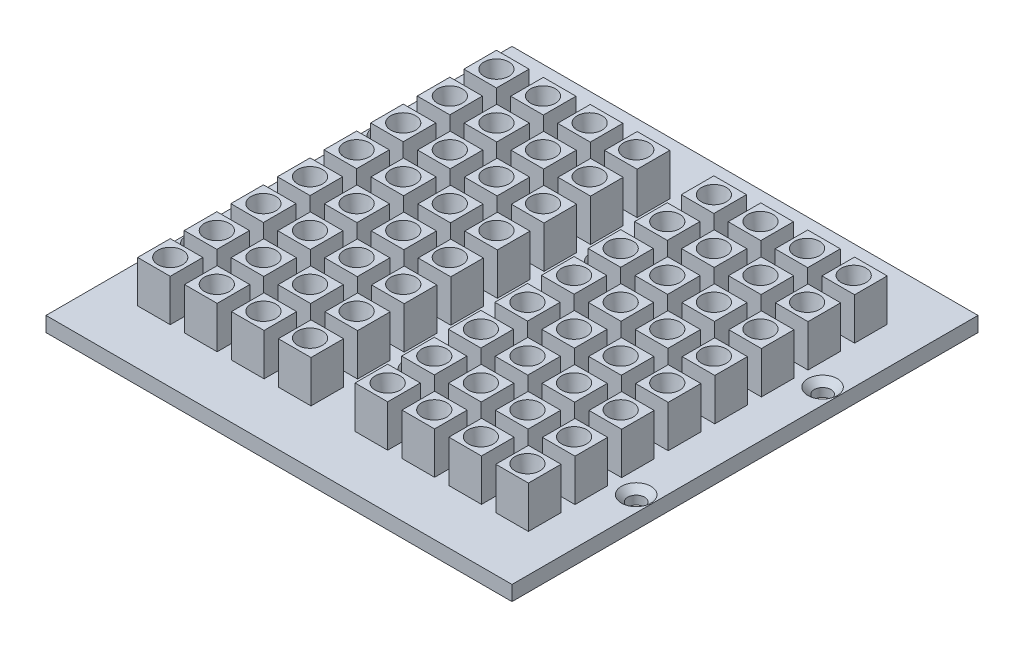
SolidWorks part; units mm, degrees
ref_plane "Front Plane" through (0, 0, 0) normal (0, 0, 1) x (1, 0, 0)
ref_plane "Top Plane" through (0, 0, 0) normal (0, 1, 0) x (1, 0, 0)
ref_plane "Right Plane" through (0, 0, 0) normal (1, 0, 0) x (0, 0, -1)
sketch "Sketch1" plane through (0, 0, 0) normal (0, 1, 0) x (1, 0, 0)
  line L1 (0, 0) -> (122, 0)
  line L2 (0, 0) -> (0, 100)
  line L3 (0, 100) -> (122, 100)
  line L4 (122, 0) -> (122, 100)
  dimension "D1" = 122
  dimension "D2" = 100
extrude "Boss-Extrude1" add sketch "Sketch1" along normal blind 3.2
sketch "Heatsink size" plane through (0, 3.2, 0) normal (0, 1, 0) x (1, 0, 0)
  line L0 (0, 100) -> (0, 0) construction
  line L1 (11, 100) -> (111, 100)
  line L2 (11, 100) -> (11, 0)
  line L3 (11, 0) -> (111, 0)
  line L4 (111, 100) -> (111, 0)
  line L5 (122, 100) -> (0, 100) construction
  dimension "D1" = 100
  dimension "D2" = 100
  dimension "D3" = 11
  dimension "D4" = 0
sketch "Peltiers" plane through (0, 3.2, 0) normal (0, 1, 0) x (1, 0, 0)
  line L0 (11, 100) -> (111, 100) construction
  line L1 (17.66, 90) -> (57.66, 90)
  line L2 (17.66, 90) -> (17.66, 50)
  line L3 (17.66, 50) -> (57.66, 50)
  line L4 (57.66, 90) -> (57.66, 50)
  line L5 (11, 100) -> (11, 0) construction
  line L6 (64.32, 90) -> (64.32, 50)
  line L7 (64.32, 90) -> (104.32, 90)
  line L8 (104.32, 90) -> (104.32, 50)
  line L9 (64.32, 50) -> (104.32, 50)
  line L10 (64.32, 50) -> (64.32, 10)
  line L11 (64.32, 50) -> (104.32, 50)
  line L12 (104.32, 50) -> (104.32, 10)
  line L13 (64.32, 10) -> (104.32, 10)
  line L14 (17.66, 50) -> (17.66, 10)
  line L15 (17.66, 50) -> (57.66, 50)
  line L16 (57.66, 50) -> (57.66, 10)
  line L17 (17.66, 10) -> (57.66, 10)
  line L18 (17.66, 90) -> (64.32, 90) construction
  dimension "D1" = 40
  dimension "D2" = 40
  dimension "D3" = 10
  dimension "D4" = 6.66
  dimension "D6" = 46.66
  dimension "D5" = 2
  dimension "D7" = 2
sketch "Sketch4" plane through (0, 3.2, 0) normal (0, 1, 0) x (1, 0, 0)
  line L0 (11, 100) -> (111, 100) construction
  line L1 (11, 100) -> (11, 0) construction
  line L2 (14.33, 70) -> (60.99, 70) construction
  circle A0 centre (14.33, 70) radius 2
  circle A1 centre (60.99, 70) radius 2
  circle A2 centre (107.65, 70) radius 2
  circle A3 centre (60.99, 30) radius 2
  circle A4 centre (107.65, 30) radius 2
  circle A5 centre (14.33, 30) radius 2
  dimension "D1" = 30
  dimension "D2" = 3.33
  dimension "D4" = 46.66
  dimension "D3" = 3
hole_wizard "M3 Block Mounting holes" positions "3DSketch1" profile "Sketch5" countersink size "M3" standard "ANSI Metric" end condition through all
sketch3d "3DSketch1"
  point P0 (14.33, 3.2, -70)
  point P3 (60.99, 3.2, -70)
  point P6 (107.65, 3.2, -70)
  point P9 (107.65, 3.2, -30)
  point P12 (60.99, 3.2, -30)
  point P15 (14.33, 3.2, -30)
sketch "Sketch5" plane through (14.33, 3.2, -70) normal (1, 0, 0) x (0, 0, 1)
  line L0 (0, 0) -> (0, 3.2)
  line L1 (0, 3.2) -> (1.8, 3.2)
  line L2 (1.8, 3.2) -> (1.8, 1.35)
  line L3 (1.8, 1.35) -> (3.15, 0)
  line L5 (3.15, 0) -> (0, 0)
  line L6 (-1.8, 1.35) -> (-3.15, 0) construction
  line L11 (0, -6.35) -> (0, 107.95) construction
  dimension "Thru Hole Dia." = 3.6
  dimension "Thru Hole Depth" = 3.2
  dimension "Near C'Sink Dia." = 6.3
  dimension "Near C'Sink Angle" = 90
sketch "Sketch6" plane through (0, 3.2, 0) normal (0, 1, 0) x (1, 0, 0)
  line L0 (0, 100) -> (0, 0) construction
  line L1 (122, 100) -> (0, 100) construction
  circle A0 centre (5, 94) radius 2.4675
  circle A1 centre (117, 94) radius 2.4675
  circle A2 centre (117, 7) radius 2.4675
  circle A3 centre (5, 7) radius 2.4675
  dimension "D1" = 5
  dimension "D2" = 6
  dimension "D3" = 2
hole_wizard "M3 Hsink Mounting holes" [suppressed] positions "3DSketch2" profile "Sketch7" countersink size "M3" standard "ANSI Metric"
sketch3d "3DSketch2" [suppressed]
  point P0 (5, 3.2, -94)
  point P3 (117, 3.2, -94)
  point P6 (117, 3.2, -7)
  point P9 (5, 3.2, -7)
sketch "Sketch7" [suppressed] plane through (5, 3.2, -94) normal (1, 0, 0) x (0, 0, 1)
  line L0 (0, 0) -> (0, 3.2)
  line L1 (0, 3.2) -> (1.8, 3.2)
  line L2 (1.8, 3.2) -> (1.8, 1.35)
  line L3 (1.8, 1.35) -> (3.15, 0)
  line L5 (3.15, 0) -> (0, 0)
  line L6 (-1.8, 1.35) -> (-3.15, 0) construction
  line L11 (0, -6.35) -> (0, 107.95) construction
  dimension "Thru Hole Dia." = 3.6
  dimension "Thru Hole Depth" = 3.2
  dimension "Near C'Sink Dia." = 6.3
  dimension "Near C'Sink Angle" = 90
sketch "WellsSquare" plane through (0, 3.2, 0) normal (0, 1, 0) x (1, 0, 0)
  line L0 (17.66, 90) -> (57.66, 90) construction
  line L1 (19.06, 88.6) -> (26.06, 88.6)
  line L2 (19.06, 88.6) -> (19.06, 81.6)
  line L3 (19.06, 81.6) -> (26.06, 81.6)
  line L4 (26.06, 88.6) -> (26.06, 81.6)
  line L5 (17.66, 90) -> (17.66, 50) construction
  line L6 (29.1267, 88.6) -> (29.1267, 81.6)
  line L7 (29.1267, 88.6) -> (36.1267, 88.6)
  line L8 (36.1267, 88.6) -> (36.1267, 81.6)
  line L9 (29.1267, 81.6) -> (36.1267, 81.6)
  line L10 (39.1933, 88.6) -> (39.1933, 81.6)
  line L11 (39.1933, 88.6) -> (46.1933, 88.6)
  line L12 (46.1933, 88.6) -> (46.1933, 81.6)
  line L13 (39.1933, 81.6) -> (46.1933, 81.6)
  line L14 (49.26, 88.6) -> (49.26, 81.6)
  line L15 (49.26, 88.6) -> (56.26, 88.6)
  line L16 (56.26, 88.6) -> (56.26, 81.6)
  line L17 (49.26, 81.6) -> (56.26, 81.6)
  line L18 (29.1267, 78.6) -> (29.1267, 71.6)
  line L19 (29.1267, 78.6) -> (36.1267, 78.6)
  line L20 (36.1267, 78.6) -> (36.1267, 71.6)
  line L21 (29.1267, 71.6) -> (36.1267, 71.6)
  line L22 (39.1933, 78.6) -> (39.1933, 71.6)
  line L23 (39.1933, 78.6) -> (46.1933, 78.6)
  line L24 (46.1933, 78.6) -> (46.1933, 71.6)
  line L25 (39.1933, 71.6) -> (46.1933, 71.6)
  line L26 (49.26, 78.6) -> (49.26, 71.6)
  line L27 (49.26, 78.6) -> (56.26, 78.6)
  line L28 (56.26, 78.6) -> (56.26, 71.6)
  line L29 (49.26, 71.6) -> (56.26, 71.6)
  line L30 (29.1267, 68.6) -> (29.1267, 61.6)
  line L31 (29.1267, 68.6) -> (36.1267, 68.6)
  line L32 (36.1267, 68.6) -> (36.1267, 61.6)
  line L33 (29.1267, 61.6) -> (36.1267, 61.6)
  line L34 (39.1933, 68.6) -> (39.1933, 61.6)
  line L35 (39.1933, 68.6) -> (46.1933, 68.6)
  line L36 (46.1933, 68.6) -> (46.1933, 61.6)
  line L37 (39.1933, 61.6) -> (46.1933, 61.6)
  line L38 (49.26, 68.6) -> (49.26, 61.6)
  line L39 (49.26, 68.6) -> (56.26, 68.6)
  line L40 (56.26, 68.6) -> (56.26, 61.6)
  line L41 (49.26, 61.6) -> (56.26, 61.6)
  line L42 (29.1267, 58.6) -> (29.1267, 51.6)
  line L43 (29.1267, 58.6) -> (36.1267, 58.6)
  line L44 (36.1267, 58.6) -> (36.1267, 51.6)
  line L45 (29.1267, 51.6) -> (36.1267, 51.6)
  line L46 (39.1933, 58.6) -> (39.1933, 51.6)
  line L47 (39.1933, 58.6) -> (46.1933, 58.6)
  line L48 (46.1933, 58.6) -> (46.1933, 51.6)
  line L49 (39.1933, 51.6) -> (46.1933, 51.6)
  line L50 (49.26, 58.6) -> (49.26, 51.6)
  line L51 (49.26, 58.6) -> (56.26, 58.6)
  line L52 (56.26, 58.6) -> (56.26, 51.6)
  line L53 (49.26, 51.6) -> (56.26, 51.6)
  line L54 (29.1267, 48.6) -> (29.1267, 41.6)
  line L55 (29.1267, 48.6) -> (36.1267, 48.6)
  line L56 (36.1267, 48.6) -> (36.1267, 41.6)
  line L57 (29.1267, 41.6) -> (36.1267, 41.6)
  line L58 (39.1933, 48.6) -> (39.1933, 41.6)
  line L59 (39.1933, 48.6) -> (46.1933, 48.6)
  line L60 (46.1933, 48.6) -> (46.1933, 41.6)
  line L61 (39.1933, 41.6) -> (46.1933, 41.6)
  line L62 (49.26, 48.6) -> (49.26, 41.6)
  line L63 (49.26, 48.6) -> (56.26, 48.6)
  line L64 (56.26, 48.6) -> (56.26, 41.6)
  line L65 (49.26, 41.6) -> (56.26, 41.6)
  line L66 (29.1267, 38.6) -> (29.1267, 31.6)
  line L67 (29.1267, 38.6) -> (36.1267, 38.6)
  line L68 (36.1267, 38.6) -> (36.1267, 31.6)
  line L69 (29.1267, 31.6) -> (36.1267, 31.6)
  line L70 (39.1933, 38.6) -> (39.1933, 31.6)
  line L71 (39.1933, 38.6) -> (46.1933, 38.6)
  line L72 (46.1933, 38.6) -> (46.1933, 31.6)
  line L73 (39.1933, 31.6) -> (46.1933, 31.6)
  line L74 (49.26, 38.6) -> (49.26, 31.6)
  line L75 (49.26, 38.6) -> (56.26, 38.6)
  line L76 (56.26, 38.6) -> (56.26, 31.6)
  line L77 (49.26, 31.6) -> (56.26, 31.6)
  line L78 (29.1267, 28.6) -> (29.1267, 21.6)
  line L79 (29.1267, 28.6) -> (36.1267, 28.6)
  line L80 (36.1267, 28.6) -> (36.1267, 21.6)
  line L81 (29.1267, 21.6) -> (36.1267, 21.6)
  line L82 (39.1933, 28.6) -> (39.1933, 21.6)
  line L83 (39.1933, 28.6) -> (46.1933, 28.6)
  line L84 (46.1933, 28.6) -> (46.1933, 21.6)
  line L85 (39.1933, 21.6) -> (46.1933, 21.6)
  line L86 (49.26, 28.6) -> (49.26, 21.6)
  line L87 (49.26, 28.6) -> (56.26, 28.6)
  line L88 (56.26, 28.6) -> (56.26, 21.6)
  line L89 (49.26, 21.6) -> (56.26, 21.6)
  line L90 (29.1267, 18.6) -> (29.1267, 11.6)
  line L91 (29.1267, 18.6) -> (36.1267, 18.6)
  line L92 (36.1267, 18.6) -> (36.1267, 11.6)
  line L93 (29.1267, 11.6) -> (36.1267, 11.6)
  line L94 (39.1933, 18.6) -> (39.1933, 11.6)
  line L95 (39.1933, 18.6) -> (46.1933, 18.6)
  line L96 (46.1933, 18.6) -> (46.1933, 11.6)
  line L97 (39.1933, 11.6) -> (46.1933, 11.6)
  line L98 (49.26, 18.6) -> (49.26, 11.6)
  line L99 (49.26, 18.6) -> (56.26, 18.6)
  line L100 (56.26, 18.6) -> (56.26, 11.6)
  line L101 (49.26, 11.6) -> (56.26, 11.6)
  line L102 (19.06, 78.6) -> (19.06, 71.6)
  line L103 (19.06, 78.6) -> (26.06, 78.6)
  line L104 (26.06, 78.6) -> (26.06, 71.6)
  line L105 (19.06, 71.6) -> (26.06, 71.6)
  line L106 (19.06, 68.6) -> (19.06, 61.6)
  line L107 (19.06, 68.6) -> (26.06, 68.6)
  line L108 (26.06, 68.6) -> (26.06, 61.6)
  line L109 (19.06, 61.6) -> (26.06, 61.6)
  line L110 (19.06, 58.6) -> (19.06, 51.6)
  line L111 (19.06, 58.6) -> (26.06, 58.6)
  line L112 (26.06, 58.6) -> (26.06, 51.6)
  line L113 (19.06, 51.6) -> (26.06, 51.6)
  line L114 (19.06, 48.6) -> (19.06, 41.6)
  line L115 (19.06, 48.6) -> (26.06, 48.6)
  line L116 (26.06, 48.6) -> (26.06, 41.6)
  line L117 (19.06, 41.6) -> (26.06, 41.6)
  line L118 (19.06, 38.6) -> (19.06, 31.6)
  line L119 (19.06, 38.6) -> (26.06, 38.6)
  line L120 (26.06, 38.6) -> (26.06, 31.6)
  line L121 (19.06, 31.6) -> (26.06, 31.6)
  line L122 (19.06, 28.6) -> (19.06, 21.6)
  line L123 (19.06, 28.6) -> (26.06, 28.6)
  line L124 (26.06, 28.6) -> (26.06, 21.6)
  line L125 (19.06, 21.6) -> (26.06, 21.6)
  line L126 (19.06, 18.6) -> (19.06, 11.6)
  line L127 (19.06, 18.6) -> (26.06, 18.6)
  line L128 (26.06, 18.6) -> (26.06, 11.6)
  line L129 (19.06, 11.6) -> (26.06, 11.6)
  dimension "D1" = 7
  dimension "D2" = 7
  dimension "D3" = 1.4
  dimension "D4" = 1.4
  dimension "D5" = 4
  dimension "D6" = 8
extrude "Boss-Extrude4" add sketch "WellsSquare" along normal blind 9
sketch "WellHoles" plane through (0, 12.2, 0) normal (0, 1, 0) x (1, 0, 0)
  line L0 (19.06, 81.6) -> (26.06, 81.6) construction
  line L1 (26.06, 81.6) -> (26.06, 88.6) construction
  circle A0 centre (22.56, 85.1) radius 2.676
  circle A1 centre (32.56, 85.1) radius 2.676
  circle A2 centre (42.56, 85.1) radius 2.676
  circle A3 centre (52.56, 85.1) radius 2.676
  circle A4 centre (32.56, 75.1) radius 2.676
  circle A5 centre (42.56, 75.1) radius 2.676
  circle A6 centre (52.56, 75.1) radius 2.676
  circle A7 centre (32.56, 65.1) radius 2.676
  circle A8 centre (42.56, 65.1) radius 2.676
  circle A9 centre (52.56, 65.1) radius 2.676
  circle A10 centre (32.56, 55.1) radius 2.676
  circle A11 centre (42.56, 55.1) radius 2.676
  circle A12 centre (52.56, 55.1) radius 2.676
  circle A13 centre (32.56, 45.1) radius 2.676
  circle A14 centre (42.56, 45.1) radius 2.676
  circle A15 centre (52.56, 45.1) radius 2.676
  circle A16 centre (32.56, 35.1) radius 2.676
  circle A17 centre (42.56, 35.1) radius 2.676
  circle A18 centre (52.56, 35.1) radius 2.676
  circle A19 centre (32.56, 25.1) radius 2.676
  circle A20 centre (42.56, 25.1) radius 2.676
  circle A21 centre (52.56, 25.1) radius 2.676
  circle A22 centre (32.56, 15.1) radius 2.676
  circle A23 centre (42.56, 15.1) radius 2.676
  circle A24 centre (52.56, 15.1) radius 2.676
  circle A25 centre (22.56, 75.1) radius 2.676
  circle A26 centre (22.56, 65.1) radius 2.676
  circle A27 centre (22.56, 55.1) radius 2.676
  circle A28 centre (22.56, 45.1) radius 2.676
  circle A29 centre (22.56, 35.1) radius 2.676
  circle A30 centre (22.56, 25.1) radius 2.676
  circle A31 centre (22.56, 15.1) radius 2.676
  point P4 (22.56, 81.6)
  dimension "D1" = 3.5
  dimension "D2" = 3.5
  dimension "D3" = 4
extrude "Cut-Extrude1" cut sketch "WellHoles" against normal blind 11.176 draft 8.75
sketch "Sketch16" plane through (0, 3.2, 0) normal (0, 1, 0) x (1, 0, 0)
  line L1 (65.72, 88.6) -> (72.72, 88.6)
  line L2 (65.72, 88.6) -> (65.72, 81.6)
  line L3 (65.72, 81.6) -> (72.72, 81.6)
  line L4 (72.72, 88.6) -> (72.72, 81.6)
  line L6 (75.7867, 88.6) -> (75.7867, 81.6)
  line L7 (75.7867, 88.6) -> (82.7867, 88.6)
  line L8 (82.7867, 88.6) -> (82.7867, 81.6)
  line L9 (75.7867, 81.6) -> (82.7867, 81.6)
  line L10 (85.8533, 88.6) -> (85.8533, 81.6)
  line L11 (85.8533, 88.6) -> (92.8533, 88.6)
  line L12 (92.8533, 88.6) -> (92.8533, 81.6)
  line L13 (85.8533, 81.6) -> (92.8533, 81.6)
  line L14 (95.92, 88.6) -> (95.92, 81.6)
  line L15 (95.92, 88.6) -> (102.92, 88.6)
  line L16 (102.92, 88.6) -> (102.92, 81.6)
  line L17 (95.92, 81.6) -> (102.92, 81.6)
  line L18 (75.7867, 78.6) -> (75.7867, 71.6)
  line L19 (75.7867, 78.6) -> (82.7867, 78.6)
  line L20 (82.7867, 78.6) -> (82.7867, 71.6)
  line L21 (75.7867, 71.6) -> (82.7867, 71.6)
  line L22 (85.8533, 78.6) -> (85.8533, 71.6)
  line L23 (85.8533, 78.6) -> (92.8533, 78.6)
  line L24 (92.8533, 78.6) -> (92.8533, 71.6)
  line L25 (85.8533, 71.6) -> (92.8533, 71.6)
  line L26 (95.92, 78.6) -> (95.92, 71.6)
  line L27 (95.92, 78.6) -> (102.92, 78.6)
  line L28 (102.92, 78.6) -> (102.92, 71.6)
  line L29 (95.92, 71.6) -> (102.92, 71.6)
  line L30 (75.7867, 68.6) -> (75.7867, 61.6)
  line L31 (75.7867, 68.6) -> (82.7867, 68.6)
  line L32 (82.7867, 68.6) -> (82.7867, 61.6)
  line L33 (75.7867, 61.6) -> (82.7867, 61.6)
  line L34 (85.8533, 68.6) -> (85.8533, 61.6)
  line L35 (85.8533, 68.6) -> (92.8533, 68.6)
  line L36 (92.8533, 68.6) -> (92.8533, 61.6)
  line L37 (85.8533, 61.6) -> (92.8533, 61.6)
  line L38 (95.92, 68.6) -> (95.92, 61.6)
  line L39 (95.92, 68.6) -> (102.92, 68.6)
  line L40 (102.92, 68.6) -> (102.92, 61.6)
  line L41 (95.92, 61.6) -> (102.92, 61.6)
  line L42 (75.7867, 58.6) -> (75.7867, 51.6)
  line L43 (75.7867, 58.6) -> (82.7867, 58.6)
  line L44 (82.7867, 58.6) -> (82.7867, 51.6)
  line L45 (75.7867, 51.6) -> (82.7867, 51.6)
  line L46 (85.8533, 58.6) -> (85.8533, 51.6)
  line L47 (85.8533, 58.6) -> (92.8533, 58.6)
  line L48 (92.8533, 58.6) -> (92.8533, 51.6)
  line L49 (85.8533, 51.6) -> (92.8533, 51.6)
  line L50 (95.92, 58.6) -> (95.92, 51.6)
  line L51 (95.92, 58.6) -> (102.92, 58.6)
  line L52 (102.92, 58.6) -> (102.92, 51.6)
  line L53 (95.92, 51.6) -> (102.92, 51.6)
  line L54 (75.7867, 48.6) -> (75.7867, 41.6)
  line L55 (75.7867, 48.6) -> (82.7867, 48.6)
  line L56 (82.7867, 48.6) -> (82.7867, 41.6)
  line L57 (75.7867, 41.6) -> (82.7867, 41.6)
  line L58 (85.8533, 48.6) -> (85.8533, 41.6)
  line L59 (85.8533, 48.6) -> (92.8533, 48.6)
  line L60 (92.8533, 48.6) -> (92.8533, 41.6)
  line L61 (85.8533, 41.6) -> (92.8533, 41.6)
  line L62 (95.92, 48.6) -> (95.92, 41.6)
  line L63 (95.92, 48.6) -> (102.92, 48.6)
  line L64 (102.92, 48.6) -> (102.92, 41.6)
  line L65 (95.92, 41.6) -> (102.92, 41.6)
  line L66 (75.7867, 38.6) -> (75.7867, 31.6)
  line L67 (75.7867, 38.6) -> (82.7867, 38.6)
  line L68 (82.7867, 38.6) -> (82.7867, 31.6)
  line L69 (75.7867, 31.6) -> (82.7867, 31.6)
  line L70 (85.8533, 38.6) -> (85.8533, 31.6)
  line L71 (85.8533, 38.6) -> (92.8533, 38.6)
  line L72 (92.8533, 38.6) -> (92.8533, 31.6)
  line L73 (85.8533, 31.6) -> (92.8533, 31.6)
  line L74 (95.92, 38.6) -> (95.92, 31.6)
  line L75 (95.92, 38.6) -> (102.92, 38.6)
  line L76 (102.92, 38.6) -> (102.92, 31.6)
  line L77 (95.92, 31.6) -> (102.92, 31.6)
  line L78 (75.7867, 28.6) -> (75.7867, 21.6)
  line L79 (75.7867, 28.6) -> (82.7867, 28.6)
  line L80 (82.7867, 28.6) -> (82.7867, 21.6)
  line L81 (75.7867, 21.6) -> (82.7867, 21.6)
  line L82 (85.8533, 28.6) -> (85.8533, 21.6)
  line L83 (85.8533, 28.6) -> (92.8533, 28.6)
  line L84 (92.8533, 28.6) -> (92.8533, 21.6)
  line L85 (85.8533, 21.6) -> (92.8533, 21.6)
  line L86 (95.92, 28.6) -> (95.92, 21.6)
  line L87 (95.92, 28.6) -> (102.92, 28.6)
  line L88 (102.92, 28.6) -> (102.92, 21.6)
  line L89 (95.92, 21.6) -> (102.92, 21.6)
  line L90 (75.7867, 18.6) -> (75.7867, 11.6)
  line L91 (75.7867, 18.6) -> (82.7867, 18.6)
  line L92 (82.7867, 18.6) -> (82.7867, 11.6)
  line L93 (75.7867, 11.6) -> (82.7867, 11.6)
  line L94 (85.8533, 18.6) -> (85.8533, 11.6)
  line L95 (85.8533, 18.6) -> (92.8533, 18.6)
  line L96 (92.8533, 18.6) -> (92.8533, 11.6)
  line L97 (85.8533, 11.6) -> (92.8533, 11.6)
  line L98 (95.92, 18.6) -> (95.92, 11.6)
  line L99 (95.92, 18.6) -> (102.92, 18.6)
  line L100 (102.92, 18.6) -> (102.92, 11.6)
  line L101 (95.92, 11.6) -> (102.92, 11.6)
  line L102 (65.72, 78.6) -> (65.72, 71.6)
  line L103 (65.72, 78.6) -> (72.72, 78.6)
  line L104 (72.72, 78.6) -> (72.72, 71.6)
  line L105 (65.72, 71.6) -> (72.72, 71.6)
  line L106 (65.72, 68.6) -> (65.72, 61.6)
  line L107 (65.72, 68.6) -> (72.72, 68.6)
  line L108 (72.72, 68.6) -> (72.72, 61.6)
  line L109 (65.72, 61.6) -> (72.72, 61.6)
  line L110 (65.72, 58.6) -> (65.72, 51.6)
  line L111 (65.72, 58.6) -> (72.72, 58.6)
  line L112 (72.72, 58.6) -> (72.72, 51.6)
  line L113 (65.72, 51.6) -> (72.72, 51.6)
  line L114 (65.72, 48.6) -> (65.72, 41.6)
  line L115 (65.72, 48.6) -> (72.72, 48.6)
  line L116 (72.72, 48.6) -> (72.72, 41.6)
  line L117 (65.72, 41.6) -> (72.72, 41.6)
  line L118 (65.72, 38.6) -> (65.72, 31.6)
  line L119 (65.72, 38.6) -> (72.72, 38.6)
  line L120 (72.72, 38.6) -> (72.72, 31.6)
  line L121 (65.72, 31.6) -> (72.72, 31.6)
  line L122 (65.72, 28.6) -> (65.72, 21.6)
  line L123 (65.72, 28.6) -> (72.72, 28.6)
  line L124 (72.72, 28.6) -> (72.72, 21.6)
  line L125 (65.72, 21.6) -> (72.72, 21.6)
  line L126 (65.72, 18.6) -> (65.72, 11.6)
  line L127 (65.72, 18.6) -> (72.72, 18.6)
  line L128 (72.72, 18.6) -> (72.72, 11.6)
  line L129 (65.72, 11.6) -> (72.72, 11.6)
  line L130 (64.32, 90) -> (104.32, 90) construction
  line L131 (64.32, 90) -> (64.32, 50) construction
  dimension "D1" = 7
  dimension "D2" = 7
  dimension "D3" = 1.4
  dimension "D4" = 1.4
  dimension "D5" = 4
  dimension "D6" = 8
extrude "Boss-Extrude5" add sketch "Sketch16" along normal blind 9
sketch "Sketch18" plane through (0, 12.2, 0) normal (0, 1, 0) x (1, 0, 0)
  line L0 (72.72, 88.6) -> (65.72, 88.6) construction
  line L2 (65.72, 88.6) -> (65.72, 81.6) construction
  circle A0 centre (69.22, 85.1) radius 2.675
  circle A1 centre (79.22, 85.1) radius 2.675
  circle A2 centre (89.22, 85.1) radius 2.675
  circle A3 centre (99.22, 85.1) radius 2.675
  circle A4 centre (79.22, 75.1) radius 2.675
  circle A5 centre (89.22, 75.1) radius 2.675
  circle A6 centre (99.22, 75.1) radius 2.675
  circle A7 centre (79.22, 65.1) radius 2.675
  circle A8 centre (89.22, 65.1) radius 2.675
  circle A9 centre (99.22, 65.1) radius 2.675
  circle A10 centre (79.22, 55.1) radius 2.675
  circle A11 centre (89.22, 55.1) radius 2.675
  circle A12 centre (99.22, 55.1) radius 2.675
  circle A13 centre (79.22, 45.1) radius 2.675
  circle A14 centre (89.22, 45.1) radius 2.675
  circle A15 centre (99.22, 45.1) radius 2.675
  circle A16 centre (79.22, 35.1) radius 2.675
  circle A17 centre (89.22, 35.1) radius 2.675
  circle A18 centre (99.22, 35.1) radius 2.675
  circle A19 centre (79.22, 25.1) radius 2.675
  circle A20 centre (89.22, 25.1) radius 2.675
  circle A21 centre (99.22, 25.1) radius 2.675
  circle A22 centre (79.22, 15.1) radius 2.675
  circle A23 centre (89.22, 15.1) radius 2.675
  circle A24 centre (99.22, 15.1) radius 2.675
  circle A25 centre (69.22, 75.1) radius 2.675
  circle A26 centre (69.22, 65.1) radius 2.675
  circle A27 centre (69.22, 55.1) radius 2.675
  circle A28 centre (69.22, 45.1) radius 2.675
  circle A29 centre (69.22, 35.1) radius 2.675
  circle A30 centre (69.22, 25.1) radius 2.675
  circle A31 centre (69.22, 15.1) radius 2.675
  dimension "D1" = 3.5
  dimension "D2" = 3.5
  dimension "D3" = 4
extrude "Cut-Extrude2" cut sketch "Sketch18" against normal blind 11.176 draft 8.75
sketch "Block Trim" plane through (0, 3.2, 0) normal (0, 1, 0) x (1, 0, 0)
  line L1 (0, 0) -> (11, 0)
  line L2 (0, 0) -> (0, 100)
  line L3 (0, 100) -> (11, 100)
  line L4 (11, 0) -> (11, 100)
  line L5 (111, 0) -> (122, 0)
  line L6 (111, 0) -> (111, 100)
  line L7 (111, 100) -> (122, 100)
  line L8 (122, 0) -> (122, 100)
extrude "Cut-Extrude3" cut sketch "Block Trim" against normal blind 11.176
